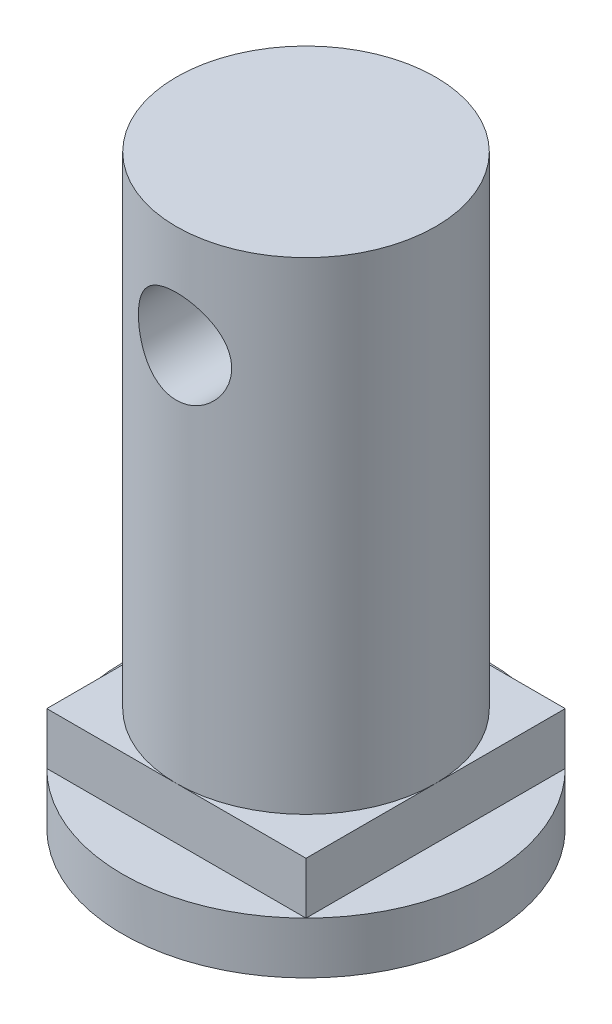
SolidWorks part; units mm, degrees
ref_plane "前视基准面" through (0, 0, 0) normal (0, 0, 1) x (1, 0, 0)
ref_plane "上视基准面" through (0, 0, 0) normal (0, 1, 0) x (1, 0, 0)
ref_plane "右视基准面" through (0, 0, 0) normal (1, 0, 0) x (0, 0, -1)
other "Configuration Table"
sketch "草图3" plane through (0, 0, 0) normal (0, 1, 0) x (1, 0, 0)
  line L1 (0, 0) -> (5, 0)
  line L2 (0, 0) -> (0, 5)
  line L3 (0, 5) -> (5, 5)
  line L4 (5, 0) -> (5, 5)
  dimension "D1" = 5
extrude "凸台-拉伸2" add sketch "草图3" along normal blind 1
sketch "草图4" plane through (0, 0, 0) normal (0, -1, 0) x (1, 0, 0)
  circle A0 centre (2.5, -2.5) radius 3.5355
extrude "凸台-拉伸3" add sketch "草图4" along normal blind 1
sketch "草图5" plane through (0, 1, 0) normal (0, 1, 0) x (1, 0, 0)
  circle A0 centre (2.5, 2.5) radius 2.5
  dimension "D1" = 5
extrude "凸台-拉伸4" add sketch "草图5" along normal blind 9.3
sketch "草图7" plane through (0, 0, -5) normal (0, 0, -1) x (-1, 0, 0)
  circle A1 centre (-2.5, 8.3) radius 0.9
extrude "切除-拉伸1" cut sketch "草图7" against normal up to next
